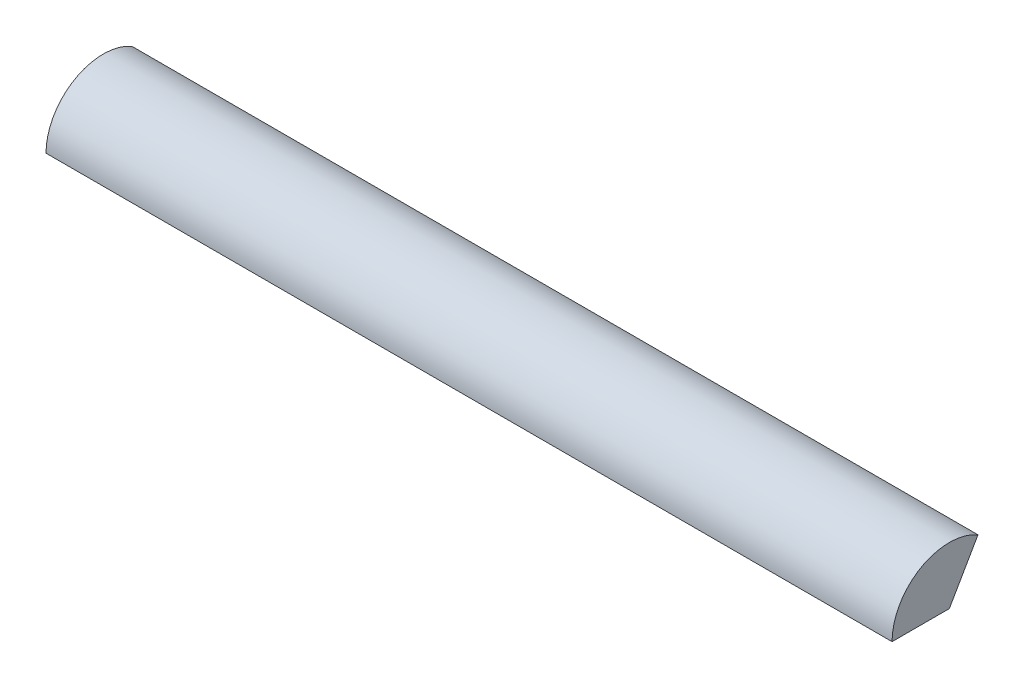
SolidWorks part; units mm, degrees
ref_plane "Front Plane" through (0, 0, 0) normal (0, 0, 1) x (1, 0, 0)
ref_plane "Top Plane" through (0, 0, 0) normal (0, 1, 0) x (1, 0, 0)
ref_plane "Right Plane" through (0, 0, 0) normal (1, 0, 0) x (0, 0, -1)
sketch "Sketch1" plane through (0, 0, 0) normal (0, 1, 0) x (1, 0, 0)
  line L0 (-520.7, -27.5) -> (-596.9, -27.5) construction
  line L1 (0, 0) -> (-609.6, 0)
  line L2 (0, 0) -> (0, -41.275)
  line L3 (0, -41.275) -> (-609.6, -41.275)
  line L4 (-609.6, 0) -> (-609.6, -41.275)
  line L5 (-596.9, 0) -> (-520.7, 0)
  line L6 (-596.9, 0) -> (-596.9, -27.5)
  line L7 (-596.9, -27.5) -> (-520.7, -27.5)
  line L8 (-520.7, 0) -> (-520.7, -27.5)
  line L9 (-596.9, -27.5) -> (-596.9, 0) construction
  line L10 (-20.7, 0) -> (-20.7, -5)
  line L11 (-520.7, -27.5) -> (-170.7, -27.5)
  line L12 (-520.7, -27.5) -> (-520.7, 0)
  line L13 (-520.7, 0) -> (-170.7, 0)
  line L14 (-170.7, -27.5) -> (-170.7, 0)
  line L15 (-20.7, -5) -> (-170.7, -27.5)
  spline S0 degree 2 poles (-520.7, -27.5) (-596.9, -27.5) (-596.9, 0) knots 0 0 0 1 1 1
  point P14 (0, 0)
  point P15 (0, 0)
  point P16 (-591.848, -34.9593)
  dimension "D1" = 609.6
  dimension "D2" = 41.275
  dimension "D3" = 76.2
  dimension "D4" = 27.5
  dimension "D5" = 350
  dimension "D6" = 5
  dimension "D7" = 150
  dimension "D8" = 12.7
revolve "Revolve1" add sketch "Sketch1" angle 120 about L1
